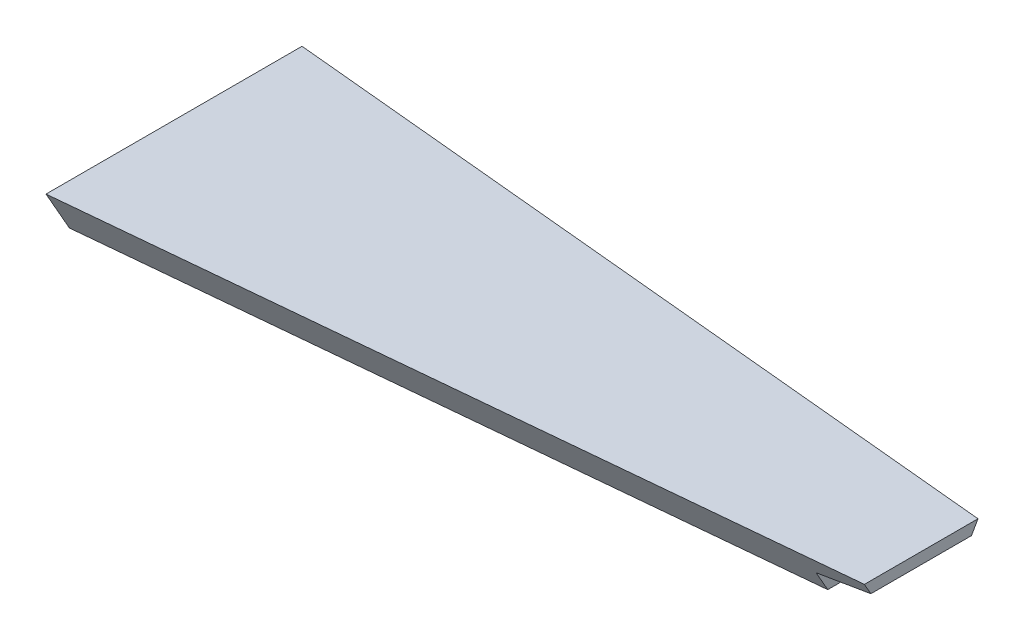
SolidWorks part; units mm, degrees
ref_plane "Front Plane" through (0, 0, 0) normal (0, 0, 1) x (1, 0, 0)
ref_plane "Top Plane" through (0, 0, 0) normal (0, 1, 0) x (1, 0, 0)
ref_plane "Right Plane" through (0, 0, 0) normal (1, 0, 0) x (0, 0, -1)
sketch "Sketch1" plane through (0, 0, 0) normal (0, 1, 0) x (1, 0, 0)
  line L0 (0, 0) -> (0, -96.9373)
  line L1 (0, -96.9373) -> (346.2442, -63.9436)
  line L2 (346.2442, -63.9436) -> (346.2442, -32.9937)
  line L3 (346.2442, -32.9937) -> (0, 0)
  dimension "Crosscut Angle" = 95.443
  dimension "Crosscut Angle 2" = 95.443
  dimension "BISW" = 30.9499
  dimension "Cut To Length" = 346.2442
extrude "Boss-Extrude1" add sketch "Sketch1" along normal blind 19.05 draft 29.547 draft outward yes
sketch "Sketch2" plane through (0, 0, 0) normal (0, 0, 1) x (1, 0, 0)
  line L0 (0, 0) -> (346.2442, 0)
  line L1 (0, 0) -> (0, 100.342)
  line L2 (346.2442, 0) -> (346.2442, 100.342)
  line L3 (0, 100.342) -> (346.2442, 100.342)
extrude "Cut-Extrude1" cut sketch "Sketch2" against normal through all and the other way through all flip side to cut
sketch "Sketch3" plane through (0, 0, 0) normal (0, 0, 1) x (1, 0, 0)
  line L0 (320.8442, 0) -> (320.8442, 9.525)
  line L1 (0, 0) -> (346.2442, 0) construction
  line L2 (320.8442, 9.525) -> (346.2442, 13.7755)
  line L3 (346.2442, 19.05) -> (346.2442, 0) construction
  line L4 (346.2442, 13.7755) -> (346.2442, 0)
  line L5 (346.2442, 0) -> (320.8442, 0)
  dimension "Dado Depth" = 9.525
  dimension "Degree of Flare (plus ninety)" = 99.5
  dimension "Dado Width" = 25.4
extrude "Cut-Extrude2" cut sketch "Sketch3" along normal through all
equation "\"Crosscut\"=88.0525"
